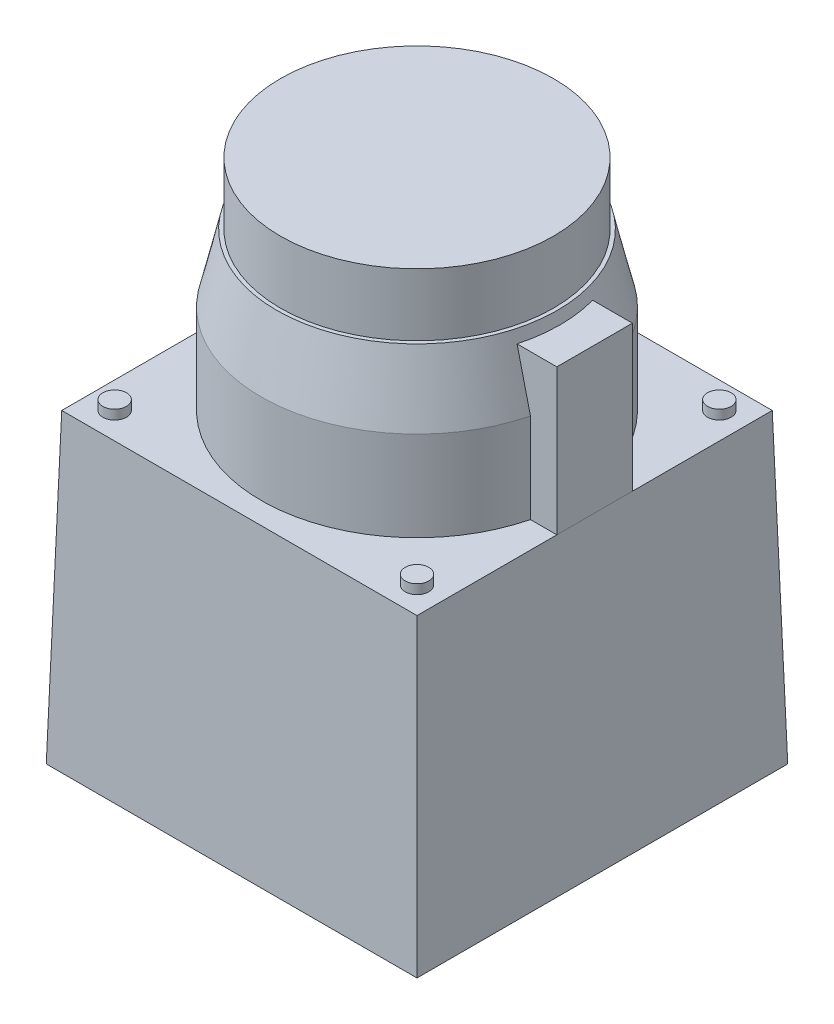
SolidWorks part; units mm, degrees
ref_plane "Front Plane" through (0, 0, 0) normal (0, 0, 1) x (1, 0, 0)
ref_plane "Top Plane" through (0, 0, 0) normal (0, 1, 0) x (1, 0, 0)
ref_plane "Right Plane" through (0, 0, 0) normal (1, 0, 0) x (0, 0, -1)
sketch "Sketch2" plane through (0, 0, 0) normal (0, 1, 0) x (1, 0, 0)
  line L1 (-24.9174, -24.9174) -> (24.9174, -24.9174)
  line L2 (-24.9174, -24.9174) -> (-24.9174, 24.9174)
  line L3 (-24.9174, 24.9174) -> (24.9174, 24.9174)
  line L4 (24.9174, -24.9174) -> (24.9174, 24.9174)
  line L5 (0, 24.9174) -> (0, -24.9174) construction
  line L6 (-24.9174, 0) -> (24.9174, 0) construction
  point P0 (0, 0)
  dimension "D1" = 49.8348
  dimension "D2" = 49.8348
sketch3d "3DSketch1" plane through (0, 0, 0) normal (0, 0, 1) x (1, 0, 0)
  dimension "D1" = 41.148
sketch "Sketch3" plane through (0, 41.148, 0) normal (0, 1, 0) x (1, 0, 0)
  line L1 (-23.876, -23.876) -> (23.876, -23.876)
  line L2 (-23.876, -23.876) -> (-23.876, 23.876)
  line L3 (-23.876, 23.876) -> (23.876, 23.876)
  line L4 (23.876, -23.876) -> (23.876, 23.876)
  line L5 (0, 23.876) -> (0, -23.876) construction
  line L6 (-23.876, 0) -> (23.876, 0) construction
  point P0 (0, 0)
  dimension "D1" = 47.752
  dimension "D2" = 47.752
loft "Loft1" add profiles "Sketch3", "Sketch2"
sketch "Sketch4" plane through (0, 41.148, 0) normal (0, 1, 0) x (1, 0, 0)
  circle A0 centre (0, 0) radius 20.955
  dimension "D1" = 41.91
extrude "Boss-Extrude1" add sketch "Sketch4" along normal blind 12.065
sketch3d "3DSketch2" plane through (0, 0, 0) normal (0, 0, 1) x (1, 0, 0)
  dimension "D1" = 62.23
sketch "Sketch5" plane through (0, 62.23, 0) normal (0, 1, 0) x (1, 0, 0)
  circle A0 centre (0, 0) radius 18.8595
  dimension "D1" = 37.719
loft "Loft2" add profiles "Sketch5" section edge at (0, 53.213, 20.955) section "Sketch5"
sketch "Sketch6" plane through (0, 62.23, 0) normal (0, 1, 0) x (1, 0, 0)
  circle A0 centre (0, 0) radius 18.3515
  dimension "D1" = 36.703
extrude "Boss-Extrude2" add sketch "Sketch6" along normal blind 8.382
sketch "Sketch7" plane through (0, 41.148, 0) normal (0, 1, 0) x (1, 0, 0)
  line L0 (23.876, 23.876) -> (-23.876, 23.876) construction
  line L1 (-23.876, 23.876) -> (-23.876, -23.876) construction
  line L2 (23.876, -23.876) -> (23.876, 23.876) construction
  line L3 (-23.876, -23.876) -> (23.876, -23.876) construction
  circle A0 centre (-20.32, 20.32) radius 1.5875
  circle A1 centre (20.32, 20.32) radius 1.5875
  circle A2 centre (-20.32, -20.32) radius 1.5875
  circle A3 centre (20.32, -20.32) radius 1.5875
  dimension "D1" = 3.175
  dimension "D6" = 3.175
  dimension "D7" = 3.175
  dimension "D10" = 3.175
  dimension "D2" = 3.556
  dimension "D3" = 3.556
  dimension "D4" = 3.556
  dimension "D5" = 3.556
  dimension "D8" = 3.556
  dimension "D9" = 3.556
  dimension "D11" = 3.556
  dimension "D12" = 3.556
extrude "Boss-Extrude3" add sketch "Sketch7" along normal blind 1.27
sketch "Sketch8" plane through (0, 41.148, 0) normal (0, 1, 0) x (1, 0, 0)
  line L0 (23.876, -23.876) -> (23.876, 23.876) construction
  line L1 (23.876, 5.08) -> (16.256, 5.08)
  line L2 (23.876, 5.08) -> (23.876, -5.08)
  line L3 (23.876, -5.08) -> (16.256, -5.08)
  line L4 (16.256, 5.08) -> (16.256, -5.08)
  line L5 (0, 0) -> (16.256, 0) construction
  point P10 (16.256, 0)
  dimension "D1" = 10.16
  dimension "D2" = 7.62
extrude "Boss-Extrude4" add sketch "Sketch8" along normal blind 19.558
